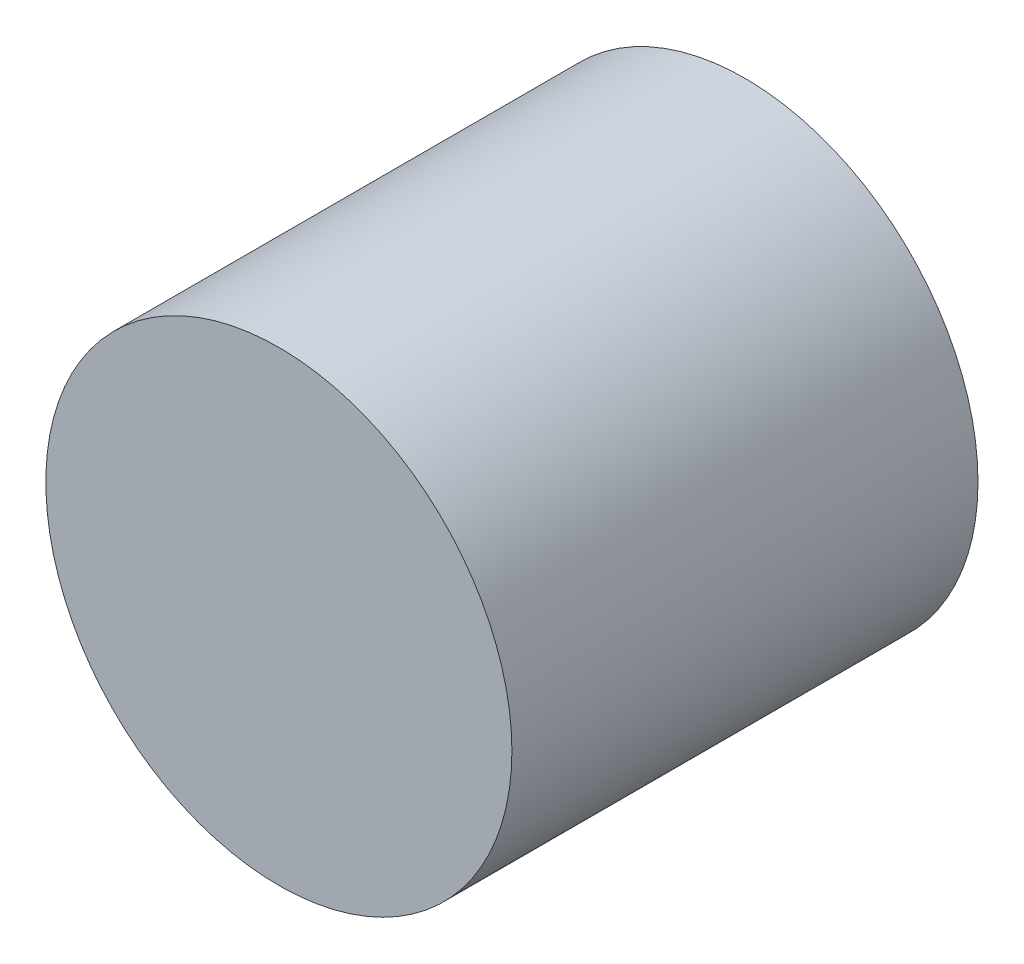
SolidWorks part; units mm, degrees
ref_plane "Front Plane" through (0, 0, 0) normal (0, 0, 1) x (1, 0, 0)
ref_plane "Top Plane" through (0, 0, 0) normal (0, 1, 0) x (1, 0, 0)
ref_plane "Right Plane" through (0, 0, 0) normal (1, 0, 0) x (0, 0, -1)
other "Configuration Table"
sketch "Sketch2" plane through (0, 0, 0) normal (0, 0, 1) x (1, 0, 0)
  circle A0 centre (0, 0) radius 3
extrude "M2p5_clearance_post" add sketch "Sketch2" along normal blind 6 from offset 0
